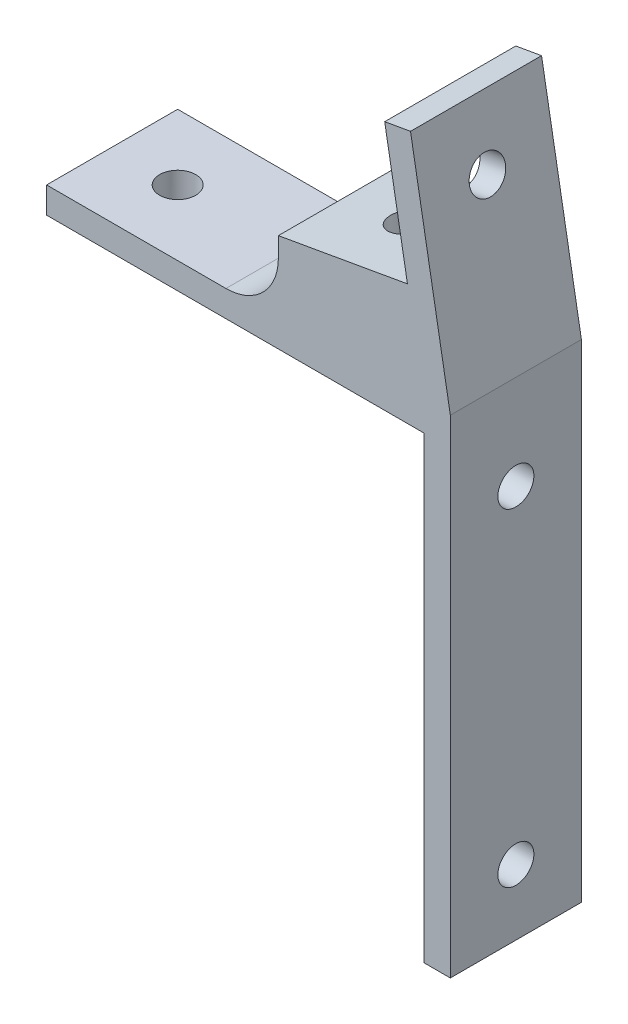
SolidWorks part; units mm, degrees
ref_plane "Front Plane" through (0, 0, 0) normal (0, 0, 1) x (1, 0, 0)
ref_plane "Top Plane" through (0, 0, 0) normal (0, 1, 0) x (1, 0, 0)
ref_plane "Right Plane" through (0, 0, 0) normal (1, 0, 0) x (0, 0, -1)
sketch "Sketch1" plane through (0, 0, 0) normal (0, 0, 1) x (1, 0, 0)
  line L0 (0, 74.3797) -> (-6.0777, 108.8479)
  line L1 (-10.0169, 108.1533) -> (-6.544, 88.4572)
  line L2 (-6.544, 88.4572) -> (-26.2401, 84.9842)
  line L3 (-26.2401, 84.9842) -> (-26.2401, 82)
  line L4 (-61.608, 70) -> (-61.608, 74)
  line L5 (-61.608, 74) -> (-34.2401, 74)
  line L6 (-10.0169, 108.1533) -> (-6.0777, 108.8479)
  line L49 (-4, 70) -> (-61.608, 70)
  line L52 (0, 74.3797) -> (0, 0)
  line L53 (0, 0) -> (-4, 0)
  line L54 (-4, 0) -> (-4, 70)
  arc A0 (-34.2401, 74) -> (-26.2401, 82) centre (-34.2401, 82) ccw
  point P3 (0, 0)
  point P5 (0, 0)
  point P9 (0, 0)
  point P11 (-26.2401, 74)
  dimension "D1" = 80
  dimension "D7" = 10.9843
  dimension "D9" = 8
  dimension "D2" = 20
  dimension "D3" = 4
  dimension "D4" = 35
  dimension "D5" = 35.3679
  dimension "D6" = 61.608
  dimension "D8" = 70
extrude "Boss-Extrude1" add sketch "Sketch1" along normal blind 20 contours L49 L4 L5 A0 L3 L2 L1 L6 L0 L52 L53 L54
sketch "Sketch6" plane through (-4, 0, 0) normal (-1, 0, 0) x (0, 0, 1)
  line L0 (0, 0) -> (0, 70) construction
  line L1 (20, 0) -> (0, 0) construction
  circle A0 centre (10, 60) radius 2.75
  circle A1 centre (10, 10) radius 2.75
  dimension "D1" = 5.5
  dimension "D2" = 10
  dimension "D3" = 10
  dimension "D4" = 60
extrude "Cut-Extrude5" cut sketch "Sketch6" against normal up to next
sketch "Sketch11" plane through (12.7197, 2.2428, 0) normal (0.9848, 0.1736, 0) x (0, 0, -1)
  line L0 (0, 73.2497) -> (0, 108.2497) construction
  line L1 (-20, 108.2497) -> (0, 108.2497) construction
  circle A0 centre (-10, 98.2497) radius 2.75
  dimension "D1" = 5.5
  dimension "D2" = 10
  dimension "D3" = 10
extrude "Cut-Extrude10" cut sketch "Sketch11" against normal up to next
sketch "Sketch12" plane through (0, 74, 0) normal (0, 1, 0) x (1, 0, 0)
  line L0 (-61.608, 0) -> (-34.2401, 0) construction
  line L1 (-61.608, -20) -> (-61.608, 0) construction
  circle A0 centre (-51.608, -10) radius 2.75
  dimension "D1" = 5.5
  dimension "D2" = 10
  dimension "D3" = 10
extrude "Cut-Extrude11" cut sketch "Sketch12" against normal up to next
sketch "Sketch13" plane through (-15.3244, 86.909, 0) normal (-0.1736, 0.9848, 0) x (0.9848, 0.1736, 0)
  line L0 (8.9159, 0) -> (-11.0841, 0) construction
  line L1 (-11.0841, -20) -> (-11.0841, 0) construction
  circle A0 centre (-1.0841, -10) radius 2.75
  dimension "D1" = 5.5
  dimension "D2" = 10
  dimension "D3" = 10
extrude "Cut-Extrude12" cut sketch "Sketch13" against normal blind 4
sketch "Sketch14" plane through (-14.6298, 82.9697, 0) normal (-0.1736, 0.9848, 0) x (0.9848, 0.1736, 0)
  circle A0 centre (-1.0841, -10) radius 5
  dimension "D1" = 10
extrude "Cut-Extrude13" cut sketch "Sketch14" against normal up to next
